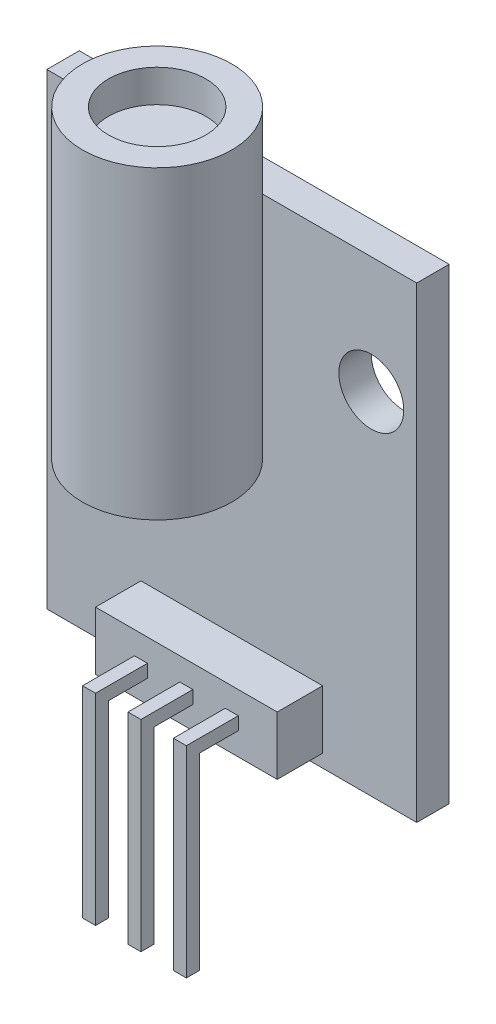
SolidWorks part; units mm, degrees
ref_plane "Front Plane" through (0, 0, 0) normal (0, 0, 1) x (1, 0, 0)
ref_plane "Top Plane" through (0, 0, 0) normal (0, 1, 0) x (1, 0, 0)
ref_plane "Right Plane" through (0, 0, 0) normal (1, 0, 0) x (0, 0, -1)
sketch "Sketch1" plane through (0, 0, 0) normal (0, 0, 1) x (1, 0, 0)
  line L1 (-7.239, 9.144) -> (7.239, 9.144)
  line L2 (-7.239, 9.144) -> (-7.239, -9.144)
  line L3 (-7.239, -9.144) -> (7.239, -9.144)
  line L4 (7.239, 9.144) -> (7.239, -9.144)
  line L5 (-7.239, 9.144) -> (7.239, -9.144) construction
  line L6 (-7.239, -9.144) -> (7.239, 9.144) construction
  point P0 (0, 0)
  dimension "D1" = 14.478
  dimension "D2" = 18.288
extrude "Boss-Extrude1" add sketch "Sketch1" along normal mid plane 1.27
sketch "Sketch2" plane through (0, 0, 0.635) normal (0, 0, 1) x (1, 0, 0)
  line L0 (-7.239, -9.144) -> (7.239, -9.144) construction
  line L1 (-3.556, -6.35) -> (3.556, -6.35)
  line L2 (-3.556, -6.35) -> (-3.556, -8.636)
  line L3 (-3.556, -8.636) -> (3.556, -8.636)
  line L4 (3.556, -6.35) -> (3.556, -8.636)
  line L5 (-3.556, -6.35) -> (3.556, -8.636) construction
  line L6 (-3.556, -8.636) -> (3.556, -6.35) construction
  point P0 (0, -7.493)
  dimension "D1" = 2.286
  dimension "D2" = 7.112
  dimension "D3" = 0.508
extrude "Boss-Extrude2" add sketch "Sketch2" along normal blind 1.778
sketch "Sketch3" plane through (0, 0, 2.413) normal (0, 0, 1) x (1, 0, 0)
  line L0 (-3.556, -6.35) -> (-3.556, -8.636) construction
  line L1 (-3.556, -7.493) -> (-1.778, -7.493) construction
  line L2 (-1.778, -7.493) -> (0, -7.493) construction
  line L3 (0, -7.493) -> (1.778, -7.493) construction
  line L4 (1.778, -7.493) -> (3.556, -7.493) construction
  line L5 (3.556, -8.636) -> (3.556, -6.35) construction
  line L7 (-2.032, -7.239) -> (-1.524, -7.239)
  line L8 (-2.032, -7.239) -> (-2.032, -7.747)
  line L9 (-2.032, -7.747) -> (-1.524, -7.747)
  line L10 (-1.524, -7.239) -> (-1.524, -7.747)
  line L11 (-2.032, -7.239) -> (-1.524, -7.747) construction
  line L12 (-2.032, -7.747) -> (-1.524, -7.239) construction
  line L13 (-0.254, -7.239) -> (0.254, -7.239)
  line L14 (-0.254, -7.239) -> (-0.254, -7.747)
  line L15 (-0.254, -7.747) -> (0.254, -7.747)
  line L16 (0.254, -7.239) -> (0.254, -7.747)
  line L17 (-0.254, -7.239) -> (0.254, -7.747) construction
  line L18 (-0.254, -7.747) -> (0.254, -7.239) construction
  line L19 (1.524, -7.239) -> (2.032, -7.239)
  line L20 (1.524, -7.239) -> (1.524, -7.747)
  line L21 (1.524, -7.747) -> (2.032, -7.747)
  line L22 (2.032, -7.239) -> (2.032, -7.747)
  line L23 (1.524, -7.239) -> (2.032, -7.747) construction
  line L24 (1.524, -7.747) -> (2.032, -7.239) construction
  dimension "D1" = 0.508
extrude "Boss-Extrude3" add sketch "Sketch3" along normal blind 2.032
sketch "Sketch4" plane through (0, -7.747, 0) normal (0, -1, 0) x (1, 0, 0)
  line L0 (-1.524, 4.445) -> (-1.524, 2.413) construction
  line L1 (-2.032, 4.445) -> (-1.524, 4.445)
  line L2 (-2.032, 4.445) -> (-2.032, 3.937)
  line L3 (-2.032, 3.937) -> (-1.524, 3.937)
  line L4 (-1.524, 4.445) -> (-1.524, 3.937)
  line L5 (-2.032, 4.445) -> (-1.524, 3.937) construction
  line L6 (-2.032, 3.937) -> (-1.524, 4.445) construction
  line L7 (-0.254, 4.445) -> (-0.254, 2.413) construction
  line L8 (-0.254, 3.937) -> (0.254, 3.937)
  line L9 (-0.254, 3.937) -> (-0.254, 4.445)
  line L10 (-0.254, 4.445) -> (0.254, 4.445)
  line L11 (0.254, 3.937) -> (0.254, 4.445)
  line L12 (-0.254, 3.937) -> (0.254, 4.445) construction
  line L13 (-0.254, 4.445) -> (0.254, 3.937) construction
  line L14 (2.032, 4.445) -> (2.032, 2.413) construction
  line L15 (1.524, 4.445) -> (2.032, 4.445)
  line L16 (1.524, 4.445) -> (1.524, 3.937)
  line L17 (1.524, 3.937) -> (2.032, 3.937)
  line L18 (2.032, 4.445) -> (2.032, 3.937)
  line L19 (1.524, 4.445) -> (2.032, 3.937) construction
  line L20 (1.524, 3.937) -> (2.032, 4.445) construction
  point P4 (-1.778, 4.191)
  point P12 (0, 4.191)
  point P20 (1.778, 4.191)
extrude "Boss-Extrude4" add sketch "Sketch4" along normal blind 7.366
sketch "Sketch5" plane through (0, 0, 0.635) normal (0, 0, 1) x (1, 0, 0)
  line L0 (0, 4.572) -> (-5.461, 4.572) construction
  line L1 (0, 4.572) -> (5.461, 4.572) construction
  line L2 (7.239, 9.144) -> (-7.239, 9.144) construction
  circle A0 centre (-5.461, 4.572) radius 1.27
  circle A1 centre (5.461, 4.572) radius 1.27
  dimension "D2" = 2.54
  dimension "D1" = 10.922
  dimension "D3" = 4.572
extrude "Cut-Extrude1" cut sketch "Sketch5" against normal through all both and the other way through all
sketch "Sketch6" plane through (0, 9.144, 0) normal (0, 1, 0) x (1, 0, 0)
  line L0 (0, -2.794) -> (0, 2.794) construction
  line L2 (3.556, -0.635) -> (-3.556, -0.635) construction
  circle A0 centre (0, -3.556) radius 2.921
  dimension "D1" = 5.842
extrude "Boss-Extrude5" add sketch "Sketch6" along normal blind 3.81 and the other way blind 8.128 separate body
sketch "Sketch7" plane through (0, 12.954, 0) normal (0, 1, 0) x (1, 0, 0)
  line L0 (0, -3.9116) -> (0, 3.9116) construction
  circle A0 centre (0, -3.556) radius 1.905
  circle A1 centre (0, -3.556) radius 2.921 construction
  dimension "D1" = 3.81
extrude "Cut-Extrude2" cut sketch "Sketch7" against normal blind 1.27
